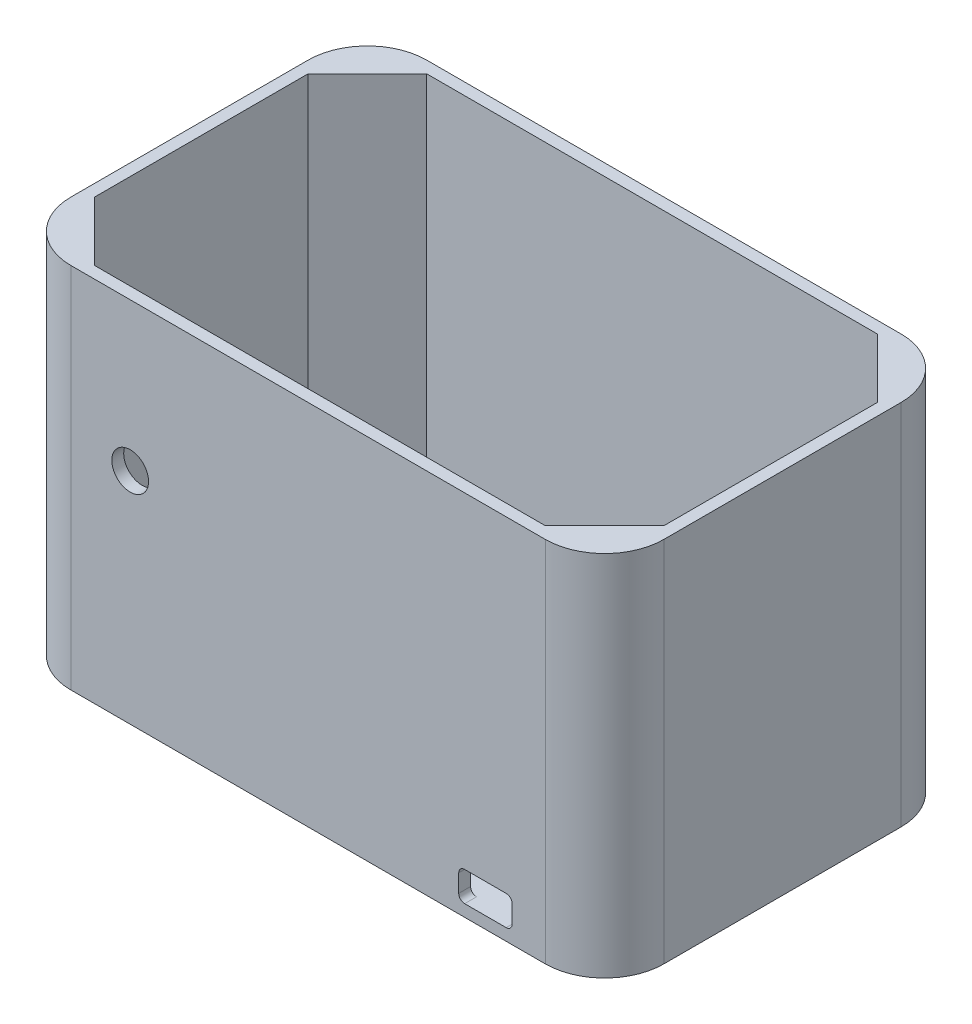
SolidWorks part; units mm, degrees
ref_plane "Ön Düzlem" through (0, 0, 0) normal (0, 0, 1) x (1, 0, 0)
ref_plane "Üst Düzlem" through (0, 0, 0) normal (0, 1, 0) x (1, 0, 0)
ref_plane "Sağ Düzlem" through (0, 0, 0) normal (1, 0, 0) x (0, 0, -1)
sketch "Çizim1" plane through (0, 0, 0) normal (0, 1, 0) x (1, 0, 0)
  line L1 (10, 0) -> (90, 0)
  line L2 (0, 10) -> (0, 50)
  line L3 (10, 60) -> (90, 60)
  line L4 (100, 10) -> (100, 50)
  arc A0 (90, 60) -> (100, 50) centre (90, 50) cw
  arc A1 (100, 10) -> (90, 0) centre (90, 10) cw
  arc A2 (10, 0) -> (0, 10) centre (10, 10) cw
  arc A3 (0, 50) -> (10, 60) centre (10, 50) cw
  point P7 (100, 60)
  point P12 (0, 0)
  point P15 (0, 60)
  dimension "D3" = 10
  dimension "D1" = 60
  dimension "D2" = 100
extrude "Yükseklik-Ekstrüzyon1" add sketch "Çizim1" along normal blind 2
sketch "Çizim2" plane through (0, 2, 0) normal (0, 1, 0) x (1, 0, 0)
  line L0 (50, 58) -> (50, 2) construction
  line L1 (10, 0) -> (90, 0)
  line L2 (0, 10) -> (0, 50)
  line L3 (10, 60) -> (90, 60)
  line L4 (100, 10) -> (100, 50)
  line L5 (12, 58) -> (88, 58)
  line L6 (2, 48) -> (2, 12)
  line L7 (12, 2) -> (88, 2)
  line L8 (98, 48) -> (98, 12)
  line L9 (12, 58) -> (12, 2) construction
  line L10 (2, 48) -> (98, 48) construction
  line L11 (12, 58) -> (2, 48)
  line L12 (88, 58) -> (98, 48)
  line L13 (2, 30) -> (98, 30) construction
  line L14 (88, 2) -> (98, 12)
  line L15 (12, 2) -> (2, 12)
  arc A0 (90, 60) -> (100, 50) centre (90, 50) cw
  arc A1 (100, 10) -> (90, 0) centre (90, 10) cw
  arc A2 (10, 0) -> (0, 10) centre (10, 10) cw
  arc A3 (0, 50) -> (10, 60) centre (10, 50) cw
  point P20 (100, 60)
  point P25 (0, 0)
  point P28 (0, 60)
  arc M9 (100, 50) -> (90, 60) centre (90, 50) ccw
  line M10 (90, 60) -> (10, 60)
  arc M11 (10, 60) -> (0, 50) centre (10, 50) ccw
  line M12 (0, 50) -> (0, 10)
  arc M13 (0, 10) -> (10, 0) centre (10, 10) ccw
  line M14 (10, 0) -> (90, 0)
  arc M15 (90, 0) -> (100, 10) centre (90, 10) ccw
  line M16 (100, 10) -> (100, 50)
  dimension "D3" = 10
  dimension "D1" = 60
  dimension "D2" = 100
  dimension "D5" = 2
  dimension "D6" = 2
  dimension "D7" = 10
  dimension "D8" = 10
extrude "Yükseklik-Ekstrüzyon2" add sketch "Çizim2" along normal blind 60 contours L7 L15 L6 L11 L5 L12 L8 L14 M16 M9 M10 M11 M12 M13 M14 M15
sketch "Çizim3" plane through (0, 0, 0) normal (0, 0, 1) x (1, 0, 0)
  line L0 (10, 62) -> (90, 62) construction
  line L1 (10, 62) -> (10, 0) construction
  line L2 (10, 0) -> (90, 0) construction
  line L9 (79.9, 7) -> (79.9, 2) construction
  line L10 (76.4, 2) -> (83.4, 2)
  line L11 (75.4, 3) -> (75.4, 6)
  line L12 (76.4, 7) -> (83.4, 7)
  line L13 (84.4, 3) -> (84.4, 6)
  circle A0 centre (20, 37) radius 3.1
  arc A1 (83.4, 7) -> (84.4, 6) centre (83.4, 6) cw
  arc A2 (83.4, 2) -> (84.4, 3) centre (83.4, 3) ccw
  arc A3 (76.4, 2) -> (75.4, 3) centre (76.4, 3) cw
  arc A4 (75.4, 6) -> (76.4, 7) centre (76.4, 6) cw
  point P24 (84.4, 7)
  point P29 (75.4, 2)
  point P32 (75.4, 7)
  dimension "D1" = 6.2
  dimension "D11" = 1
  dimension "D2" = 25
  dimension "D3" = 10
  dimension "D4" = 5
  dimension "D5" = 9
  dimension "D6" = 2
extrude "Kes-Ekstrüzyon1" cut sketch "Çizim3" against normal blind 10
